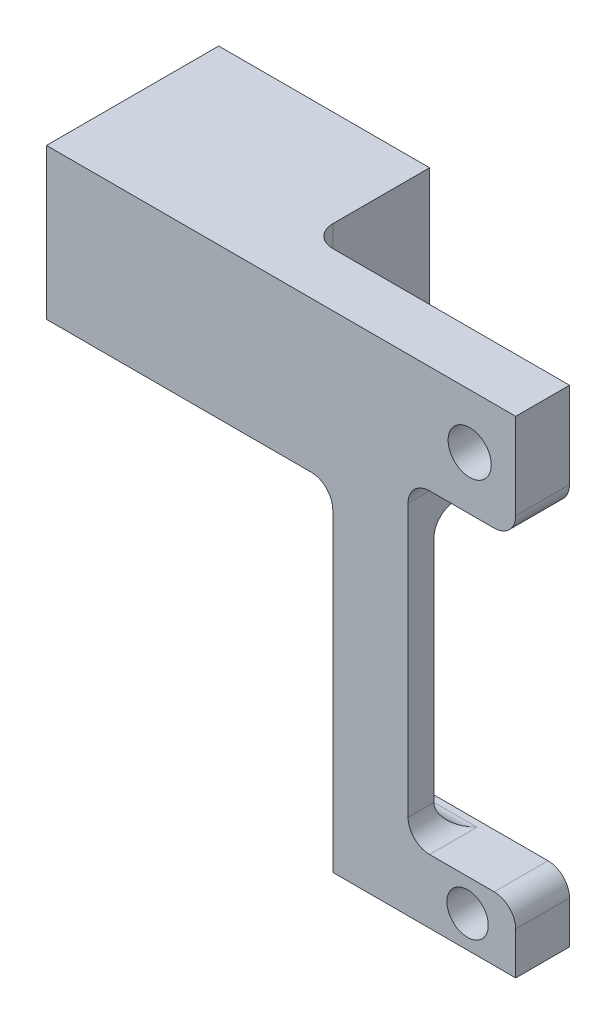
SolidWorks part; units mm, degrees
material "Custom Plastic"
ref_plane "X-Y Datum" through (0, 0, 0) normal (0, 0, 1) x (1, 0, 0)
ref_plane "X-Z Datum" through (0, 0, 0) normal (0, 1, 0) x (1, 0, 0)
ref_plane "Y-Z Datum" through (0, 0, 0) normal (1, 0, 0) x (0, 0, -1)
sketch "Sketch1" plane through (0, 0, 0) normal (0, 0, 1) x (1, 0, 0)
  line L1 (0, 0) -> (24.892, 0)
  line L2 (0, 0) -> (0, 17.78)
  line L3 (0, 17.78) -> (24.892, 17.78)
  line L4 (24.892, 0) -> (24.892, 17.78)
extrude "Boss-Extrude1" add sketch "Sketch1" along normal blind 20.32
sketch "Sketch2" plane through (24.892, 0, 0) normal (1, 0, 0) x (0, 0, -1)
  line L0 (-20.32, 17.78) -> (0, 17.78) construction
  line L1 (-20.32, 0) -> (-13.97, 0)
  line L2 (-20.32, 0) -> (-20.32, 17.78)
  line L3 (-20.32, 17.78) -> (-13.97, 17.78)
  line L4 (-13.97, 0) -> (-13.97, 17.78)
extrude "Boss-Extrude2" add sketch "Sketch2" along normal blind 17.78
sketch "Sketch16" plane through (42.672, 0, 0) normal (1, 0, 0) x (0, 0, -1)
  line L0 (-20.32, 17.78) -> (-20.32, 0) construction
  line L1 (-13.97, 17.78) -> (-20.32, 17.78)
  line L2 (-13.97, 17.78) -> (-13.97, 5.08)
  line L3 (-13.97, 5.08) -> (-20.32, 5.08)
  line L4 (-20.32, 17.78) -> (-20.32, 5.08)
extrude "Boss-Extrude11" add sketch "Sketch16" along normal blind 12.7
sketch "Sketch20" plane through (0, 0, 0) normal (0, -1, 0) x (1, 0, 0)
  line L1 (42.672, 20.32) -> (33.782, 20.32)
  line L2 (42.672, 20.32) -> (42.672, 17.272)
  line L3 (42.672, 17.272) -> (33.782, 17.272)
  line L4 (33.782, 20.32) -> (33.782, 17.272)
extrude "Boss-Extrude12" add sketch "Sketch20" along normal blind 39.624
sketch "Sketch21" plane through (0, 0, 17.272) normal (0, 0, -1) x (-1, 0, 0)
  line L1 (-42.672, -39.624) -> (-42.672, 0) construction
  line L2 (-33.782, -39.624) -> (-42.672, -39.624)
  line L3 (-33.782, -39.624) -> (-33.782, -32.0845)
  line L4 (-33.782, -32.0845) -> (-42.672, -32.0845)
  line L5 (-42.672, -39.624) -> (-42.672, -32.0845)
extrude "Boss-Extrude13" add sketch "Sketch21" along normal blind 3.302
sketch "Sketch22" plane through (42.672, 0, 0) normal (1, 0, 0) x (0, 0, -1)
  line L1 (-20.32, -39.624) -> (-13.97, -39.624)
  line L2 (-20.32, -39.624) -> (-20.32, -32.0845)
  line L3 (-20.32, -32.0845) -> (-13.97, -32.0845)
  line L4 (-13.97, -39.624) -> (-13.97, -32.0845)
extrude "Boss-Extrude14" add sketch "Sketch22" along normal blind 12.7
sketch "Sketch18" plane through (0, 0, 20.32) normal (0, 0, 1) x (1, 0, 0)
  circle A0 centre (49.9402, 11.3664) radius 2.5477
  circle A2 centre (49.6932, -35.8776) radius 2.4392
extrude "Cut-Extrude11" cut sketch "Sketch18" against normal through all
fillet "Fillet8" radius 2.54 10 edges at (33.782, 0, 18.796) (55.372, -32.0845, 17.145) (42.672, -32.0845, 18.796) (55.372, 5.08, 17.145) (42.672, 5.08, 17.145) (38.227, 0, 17.272) (33.782, -16.0422, 17.272) (33.782, -32.0845, 15.621) (38.227, -32.0845, 17.272) (24.892, 8.89, 13.97)
